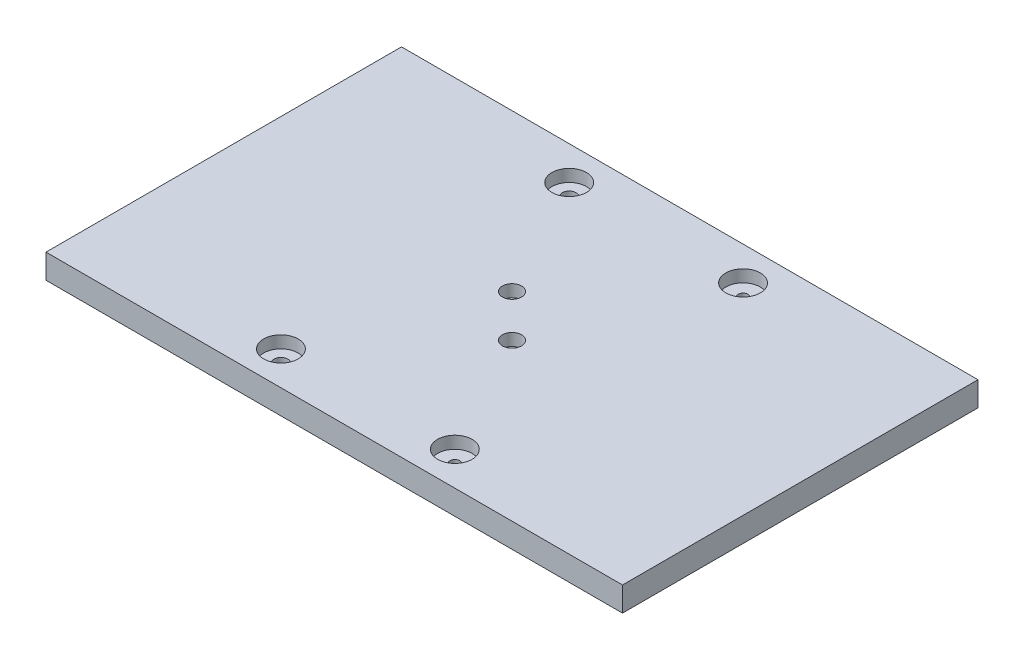
SolidWorks part; units mm, degrees
ref_plane "Front Plane" through (0, 0, 0) normal (0, 0, 1) x (1, 0, 0)
ref_plane "Top Plane" through (0, 0, 0) normal (0, 1, 0) x (1, 0, 0)
ref_plane "Right Plane" through (0, 0, 0) normal (1, 0, 0) x (0, 0, -1)
sketch "Sketch1" plane through (0, 0, 0) normal (0, 1, 0) x (1, 0, 0)
  line L0 (45.25, 45.25) -> (45.25, -45.25) construction
  line L1 (150, -92.5) -> (-150, -92.5)
  line L2 (150, -92.5) -> (150, 92.5)
  line L3 (150, 92.5) -> (-150, 92.5)
  line L4 (-150, -92.5) -> (-150, 92.5)
  line L5 (150, -92.5) -> (-150, 92.5) construction
  line L6 (150, 92.5) -> (-150, -92.5) construction
  line L7 (45.25, -75) -> (-45.25, -75) construction
  line L8 (45.25, -75) -> (45.25, 75) construction
  line L9 (45.25, 75) -> (-45.25, 75) construction
  line L10 (-45.25, -75) -> (-45.25, 75) construction
  line L11 (45.25, -75) -> (-45.25, 75) construction
  line L12 (45.25, 75) -> (-45.25, -75) construction
  line L13 (45.25, 45.25) -> (-45.25, 45.25) construction
  line L14 (-45.25, 45.25) -> (-45.25, -45.25) construction
  line L15 (45.25, -45.25) -> (-45.25, -45.25) construction
  line L16 (45.25, 45.25) -> (-45.25, -45.25) construction
  line L17 (-45.25, 45.25) -> (45.25, -45.25) construction
  line L18 (11, -11) -> (-11, -11) construction
  line L19 (11, -11) -> (11, 11) construction
  line L20 (11, 11) -> (-11, 11) construction
  line L21 (-11, -11) -> (-11, 11) construction
  line L22 (11, -11) -> (-11, 11) construction
  line L23 (11, 11) -> (-11, -11) construction
  circle A0 centre (-45.25, 75) radius 3.56
  circle A1 centre (-45.25, -75) radius 3.56
  circle A2 centre (45.25, 75) radius 2.5
  circle A3 centre (45.25, -75) radius 2.5
  circle A8 centre (-11, 11) radius 2.5
  circle A9 centre (11, 11) radius 2.5 construction
  circle A10 centre (11, -11) radius 2.5
  circle A11 centre (-11, -11) radius 2.5 construction
  point P0 (0, 0)
  point P5 (0, 0)
  point P14 (-0.6715, -0.4029)
  point P15 (0, 0)
  point P24 (0, 0)
  dimension "D3" = 7.12
  dimension "D4" = 5
  dimension "D12" = 5
  dimension "D1" = 300
  dimension "D2" = 90.5
  dimension "D5" = 90.5
  dimension "160" = 150
  dimension "D7" = 90.5
  dimension "D8" = 185
  dimension "D11" = 22
extrude "Boss-Extrude1" add sketch "Sketch1" along normal blind 12.7
sketch "Sketch2" plane through (0, 12.7, 0) normal (0, 1, 0) x (1, 0, 0)
  line L1 (150, 92.5) -> (-150, 92.5) construction
  line L4 (-150, 92.5) -> (-150, -92.5) construction
  line L5 (-150, -92.5) -> (150, -92.5) construction
  line L6 (-150, 0) -> (150, 0) construction
  line L7 (150, -92.5) -> (150, 92.5) construction
  line L11 (0, 92.5) -> (0, -92.5) construction
  circle A0 centre (-45.25, 75) radius 9
  circle A1 centre (45.25, 75) radius 9
  circle A2 centre (45.25, -75) radius 9
  circle A3 centre (-45.25, -75) radius 9
  circle A4 centre (-11, 11) radius 5
  circle A6 centre (11, -11) radius 5
  dimension "D1" = 18
  dimension "D2" = 10
  dimension "D3" = 10
extrude "Cut-Extrude1" cut sketch "Sketch2" against normal blind 6.35
